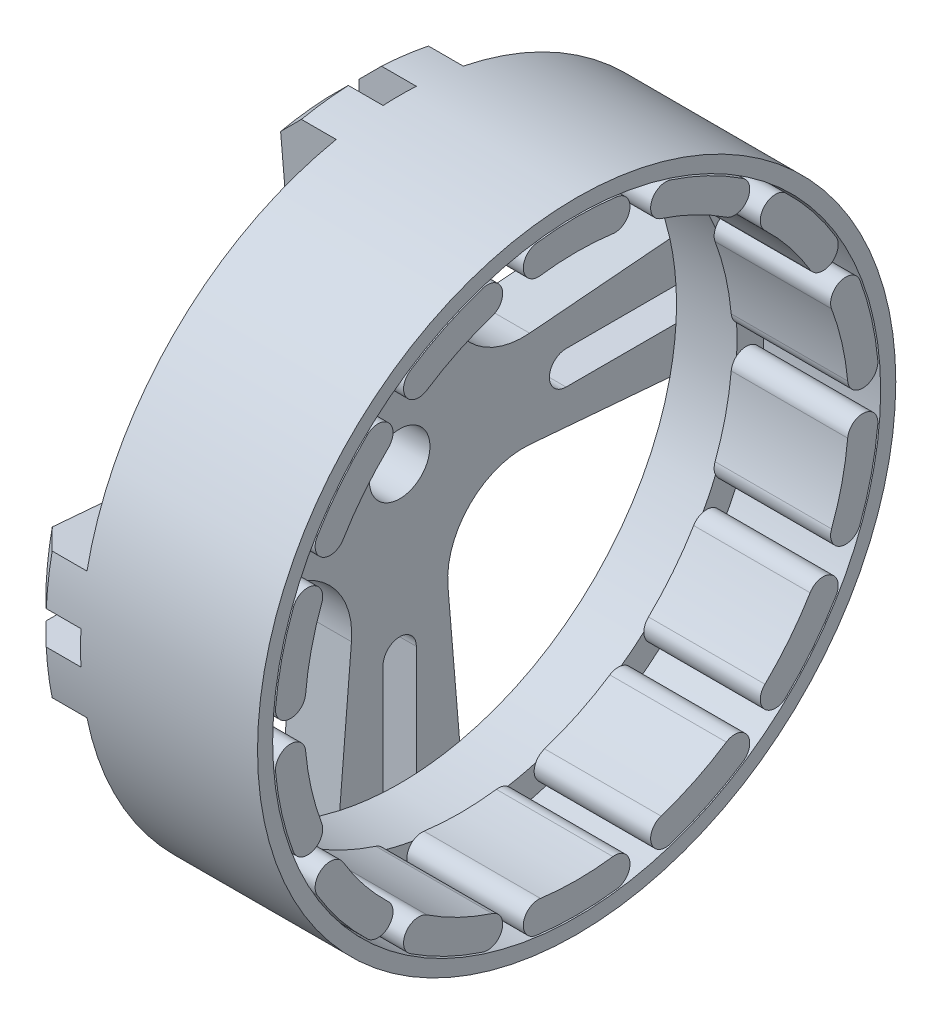
SolidWorks part; units mm, degrees
ref_plane "前视基准面" through (0, 0, 0) normal (0, 0, 1) x (1, 0, 0)
ref_plane "上视基准面" through (0, 0, 0) normal (0, 1, 0) x (1, 0, 0)
ref_plane "右视基准面" through (0, 0, 0) normal (1, 0, 0) x (0, 0, -1)
sketch "草图1" plane through (0, 0, 0) normal (0, 0, 1) x (1, 0, 0)
  line L0 (-57.3104, 21.3722) -> (-5.9619, 21.3722) construction
  line L1 (-45.6996, 21.3722) -> (-45.6996, 23.3722)
  line L2 (-43.9996, 40.9722) -> (-42.4996, 42.4722)
  line L3 (-42.4996, 42.4722) -> (-28.4996, 42.4722)
  line L4 (-28.4996, 42.4722) -> (-28.4996, 29.7222)
  line L5 (-28.4996, 29.7222) -> (-23.2996, 29.7222)
  line L6 (-23.2996, 29.7222) -> (-23.2996, 33.3722)
  line L7 (-23.2996, 33.3722) -> (-20.2996, 33.3722)
  line L8 (-20.2996, 33.3722) -> (-20.2996, 21.3722)
  line L9 (-45.6996, 23.3722) -> (-43.9996, 23.3722)
  line L10 (-43.9996, 23.3722) -> (-43.9996, 40.9722)
  line L11 (-45.6996, 21.3722) -> (-20.2996, 21.3722)
  dimension "D2" = 3
  dimension "D3" = 15.5
  dimension "D4" = 1.7
  dimension "D5" = 21.1
  dimension "D6" = 2
  dimension "D7" = 135
  dimension "D9" = 1.5
  dimension "D10" = 8.35
  dimension "D11" = 12
  dimension "D12" = 23.7
revolve "旋转1" add sketch "草图1" angle 360 about L0
sketch "草图2" plane through (-20.2996, 0, 0) normal (1, 0, 0) x (0, 0, -1)
  circle A0 centre (0, 21.3722) radius 2.5
  dimension "D1" = 5
extrude "凸台-拉伸1" add sketch "草图2" along normal blind 0.5
sketch "草图3" plane through (-20.2996, 0, 0) normal (1, 0, 0) x (0, 0, -1)
  circle A0 centre (0, 21.3722) radius 8 construction
  circle A1 centre (0, 21.3722) radius 9.5 construction
  dimension "D1" = 16
  dimension "D2" = 19
hole_wizard "M3 螺纹孔1" positions "草图5" profile "草图4" tap size "M3" standard "GB"
sketch "草图5" plane through (-20.2996, 0, 0) normal (1, 0, 0) x (0, 0, -1)
  circle A0 centre (0, 21.3722) radius 8 construction
  circle A1 centre (0, 21.3722) radius 9.5 construction
  point P0 (0, 29.3722)
  point P4 (0, 13.3722)
  point P6 (-9.4619, 22.222)
  point P10 (9.4619, 22.222)
sketch "草图4" plane through (-20.2996, 29.3722, 0) normal (0, 1, 0) x (0, 0, -1)
  line L0 (0, 0) -> (0, 3.7501)
  line L1 (0, 3.7501) -> (1.25, 2.999)
  line L2 (1.25, 2.999) -> (1.25, 0)
  line L5 (1.25, 0) -> (0, 0)
  line L10 (0, 3.7501) -> (-1.25, 2.999) construction
  line L11 (0, -6.35) -> (0, 107.95) construction
  dimension "螺纹孔钻头直径" = 2.5
  dimension "螺纹孔钻头深度" = 2.999
  dimension "导头角度" = 118
cosmetic thread "孔螺蚊线1" parameters "D1"=3, "D2"=3
cosmetic thread "孔螺蚊线2" parameters "D1"=3, "D2"=3
cosmetic thread "孔螺蚊线3" parameters "D1"=3, "D2"=3
cosmetic thread "孔螺蚊线4" parameters "D1"=3, "D2"=3
sketch "草图6" plane through (-43.9996, 0, 0) normal (-1, 0, 0) x (0, 0, 1)
  circle A0 centre (0, 21.3722) radius 6 construction
hole_wizard "M3 螺纹孔2" positions "草图8" profile "草图7" tap size "M3" standard "GB"
sketch "草图8" plane through (-43.9996, 0, 0) normal (-1, 0, 0) x (0, 0, 1)
  line L0 (-13.9377, 21.1444) -> (12.9511, 21.1444)
  circle A0 centre (0, 21.3722) radius 6 construction
  point P0 (0, 27.3722)
  point P4 (6, 21.3722)
  point P6 (0, 15.3722)
  point P8 (-6, 21.3722)
  point P18 (0, 21.3722)
sketch "草图7" plane through (-43.9996, 27.3722, 0) normal (0, 1, 0) x (0, 0, 1)
  line L0 (0, 0) -> (0, 3.7511)
  line L1 (0, 3.7511) -> (1.25, 3)
  line L2 (1.25, 3) -> (1.25, 0)
  line L5 (1.25, 0) -> (0, 0)
  line L10 (0, 3.7511) -> (-1.25, 3) construction
  line L11 (0, -6.35) -> (0, 107.95) construction
  dimension "螺纹孔钻头直径" = 2.5
  dimension "螺纹孔钻头深度" = 3
  dimension "导头角度" = 118
cosmetic thread "孔螺蚊线5" parameters "D1"=3, "D2"=3
cosmetic thread "孔螺蚊线6" parameters "D1"=3, "D2"=3
cosmetic thread "孔螺蚊线7" parameters "D1"=3, "D2"=3
cosmetic thread "孔螺蚊线8" parameters "D1"=3, "D2"=3
sketch "草图9" plane through (-43.9996, 0, 0) normal (-1, 0, 0) x (0, 0, 1)
  line L0 (0, 21.3722) -> (0, 42.4722) construction
  line L1 (0, 32.3722) -> (0, 48.9022) construction
  line L2 (-1.1, 32.3722) -> (-1.1, 48.9022)
  line L3 (1.1, 32.3722) -> (1.1, 48.9022)
  line L4 (11, 21.3722) -> (27.53, 21.3722) construction
  line L5 (11, 22.4722) -> (27.53, 22.4722)
  line L6 (11, 20.2722) -> (27.53, 20.2722)
  line L7 (0, 10.3722) -> (0, -6.1577) construction
  line L8 (1.1, 10.3722) -> (1.1, -6.1577)
  line L9 (-1.1, 10.3722) -> (-1.1, -6.1577)
  line L10 (-11, 21.3722) -> (-27.53, 21.3722) construction
  line L11 (-11, 20.2722) -> (-27.53, 20.2722)
  line L12 (-11, 22.4722) -> (-27.53, 22.4722)
  circle A0 centre (0, 21.3722) radius 21.1 construction
  arc A1 (-1.1, 32.3722) -> (1.1, 32.3722) centre (0, 32.3722) ccw
  arc A2 (1.1, 48.9022) -> (-1.1, 48.9022) centre (0, 48.9022) ccw
  arc A3 (11, 22.4722) -> (11, 20.2722) centre (11, 21.3722) ccw
  arc A4 (27.53, 20.2722) -> (27.53, 22.4722) centre (27.53, 21.3722) ccw
  arc A5 (1.1, 10.3722) -> (-1.1, 10.3722) centre (0, 10.3722) ccw
  arc A6 (-1.1, -6.1577) -> (1.1, -6.1577) centre (0, -6.1577) ccw
  arc A7 (-11, 20.2722) -> (-11, 22.4722) centre (-11, 21.3722) ccw
  arc A8 (-27.53, 22.4722) -> (-27.53, 20.2722) centre (-27.53, 21.3722) ccw
  point P9 (0, 40.6372)
  point P19 (19.265, 21.3722)
  point P26 (0, 2.1072)
  point P33 (-19.265, 21.3722)
  point P38 (0, 21.3722)
  dimension "D1" = 1.1
  dimension "D2" = 11
  dimension "D3" = 4
extrude "切除-拉伸1" cut sketch "草图9" against normal blind 3.8
sketch "草图10" plane through (-43.9996, 0, 0) normal (-1, 0, 0) x (0, 0, 1)
  line L0 (0, 21.3722) -> (-23.5675, 21.3722) construction
  line L1 (0, 21.3722) -> (-14.92, 36.2922) construction
  line L2 (-20.6778, 25.5722) -> (-8.5887, 24.5619)
  line L3 (-4.2, 42.05) -> (-3.1897, 29.9609)
  line L4 (4.2, 42.05) -> (3.1897, 29.9609)
  line L5 (20.6778, 25.5722) -> (8.5887, 24.5619)
  line L6 (0, 21.3722) -> (0, 44.9397) construction
  line L7 (0, 21.3722) -> (14.92, 36.2922) construction
  line L8 (20.6778, 17.1722) -> (8.5887, 18.1826)
  line L9 (4.2, 0.6945) -> (3.1897, 12.7835)
  line L10 (0, 21.3722) -> (23.5675, 21.3722) construction
  line L11 (0, 21.3722) -> (14.92, 6.4523) construction
  line L12 (-4.2, 0.6945) -> (-3.1897, 12.7835)
  line L13 (-20.6778, 17.1722) -> (-8.5887, 18.1826)
  line L14 (0, 21.3722) -> (0, -2.1953) construction
  line L15 (0, 21.3722) -> (-14.92, 6.4523) construction
  arc A0 (-1.1, 42.4435) -> (-21.0713, 22.4722) centre (0, 21.3722) ccw construction
  arc A1 (-4.2, 42.05) -> (-20.6778, 25.5722) centre (0, 21.3722) ccw
  arc A2 (-8.5887, 24.5619) -> (-3.1897, 29.9609) centre (-8.1723, 29.5445) ccw
  arc A3 (20.6778, 25.5722) -> (4.2, 42.05) centre (0, 21.3722) ccw
  arc A4 (3.1897, 29.9609) -> (8.5887, 24.5619) centre (8.1723, 29.5445) ccw
  arc A5 (4.2, 0.6945) -> (20.6778, 17.1722) centre (0, 21.3722) ccw
  arc A6 (8.5887, 18.1826) -> (3.1897, 12.7835) centre (8.1723, 13.1999) ccw
  arc A7 (-20.6778, 17.1722) -> (-4.2, 0.6945) centre (0, 21.3722) ccw
  arc A8 (-3.1897, 12.7835) -> (-8.5887, 18.1826) centre (-8.1723, 13.1999) ccw
  point P12 (-2.6973, 24.0695)
  point P37 (0, 21.3722)
  dimension "D3" = 5
  dimension "D1" = 45
  dimension "D2" = 4.2
  dimension "D4" = 4
extrude "切除-拉伸2" cut sketch "草图10" against normal blind 3.8
sketch "草图11" plane through (-20.2996, 0, 0) normal (1, 0, 0) x (0, 0, -1)
  circle A0 centre (0, 21.3722) radius 4.75
  circle A1 centre (0, 21.3722) radius 2.5
  dimension "D1" = 9.5
extrude "切除-拉伸3" cut sketch "草图11" against normal blind 1
sketch "草图12" plane through (-40.1996, 0, 0) normal (-1, 0, 0) x (0, 0, 1)
  circle A0 centre (0, 21.3722) radius 18.3
  dimension "D1" = 36.6
extrude "切除-拉伸4" cut sketch "草图12" against normal through all
sketch "草图13" plane through (-28.4996, 0, 0) normal (1, 0, 0) x (0, 0, -1)
  circle A0 centre (0, 21.3722) radius 20.1
  circle A1 centre (0, 21.3722) radius 21.1 construction
  dimension "D1" = 1
extrude "切除-拉伸5" cut sketch "草图13" against normal offset from surface (7.7 mm away) 4
sketch "草图14" plane through (-36.1996, 0, 0) normal (1, 0, 0) x (0, 0, -1)
  line L0 (0, 21.3722) -> (0, 41.4722) construction
  line L1 (0, 21.3722) -> (-4.4727, 40.9683) construction
  line L2 (0, 21.3722) -> (4.4727, 40.9683) construction
  circle A0 centre (0, 21.3722) radius 20.1 construction
  arc A1 (-2.5269, 40.1968) -> (2.5269, 40.1968) centre (0, 21.3722) cw construction
  arc A2 (2.6599, 41.1879) -> (-2.6599, 41.1879) centre (0, 21.3722) ccw
  arc A3 (2.3939, 39.2057) -> (-2.3939, 39.2057) centre (0, 21.3722) ccw
  arc A4 (2.3939, 39.2057) -> (2.6599, 41.1879) centre (2.5269, 40.1968) ccw
  arc A5 (-2.6599, 41.1879) -> (-2.3939, 39.2057) centre (-2.5269, 40.1968) ccw
  point P10 (0, 40.3656)
  dimension "D3" = 1
  dimension "D1" = 12.857
  dimension "D2" = 12.857
extrude "凸台-拉伸2" add sketch "草图14" along normal up to surface (7.7 mm away)
pattern_circular "阵列(圆周)1" count 14 over 360 about axis through (0, 21.3722, 0) along (1, 0, 0) of "凸台-拉伸2"
sketch "草图15" plane through (-45.6996, 0, 0) normal (-1, 0, 0) x (0, 0, 1)
  circle A0 centre (0, 21.3722) radius 2
extrude "切除-拉伸6" cut sketch "草图15" against normal through all
sketch "草图16" plane through (-43.9996, 0, 0) normal (-1, 0, 0) x (0, 0, 1)
  line L0 (0, 21.3722) -> (21.1, 21.3722) construction
  line L1 (0, 21.3722) -> (11.1257, 32.4979) construction
  arc A0 (21.0713, 20.2722) -> (21.0713, 22.4722) centre (0, 21.3722) ccw construction
  dimension "D1" = 45
ref_plane "基准面1" through (0, 15.3229, 15.3229) normal (0, 0.7071, 0.7071) x (1, 0, 0)
sketch "草图17" plane through (0, 15.3229, 15.3229) normal (0, 0.7071, 0.7071) x (1, 0, 0)
  line L3 (-28.4996, 36.2124) -> (-28.4996, -5.9876) construction
  line L4 (-28.4996, 15.1124) -> (-43.9996, 15.1124) construction
  line L5 (-43.9996, 18.9302) -> (-43.9996, 11.2947) construction
  circle A0 centre (-42.1281, 15.1124) radius 0.7743
  dimension "D1" = 42.2
ref_plane "基准面2" through (0, 16.03, 16.03) normal (0, 0.7071, 0.7071) x (1, 0, 0)
hole_wizard "M2.5 螺纹孔3" positions "草图23" profile "草图22" tap size "M2.5" standard "GB"
sketch "草图23" plane through (0, 16.03, 16.03) normal (0, 0.7071, 0.7071) x (1, 0, 0)
  point P0 (-42.1281, 15.1124)
sketch "草图22" plane through (-42.1281, 26.7161, 5.3439) normal (1, 0, 0) x (0, -0.7071, 0.7071)
  line L0 (0, 0) -> (0, 8.1723)
  line L1 (0, 8.1723) -> (1.025, 7.5564)
  line L2 (1.025, 7.5564) -> (1.025, 0)
  line L5 (1.025, 0) -> (0, 0)
  line L10 (0, 8.1723) -> (-1.025, 7.5564) construction
  line L11 (0, -6.35) -> (0, 107.95) construction
  dimension "螺纹孔钻头直径" = 2.05
  dimension "螺纹孔钻头深度" = 7.5564
  dimension "导头角度" = 118
cosmetic thread "孔螺蚊线9" parameters "D1"=5, "D2"=2.5
equation "\"。5\"=3"
